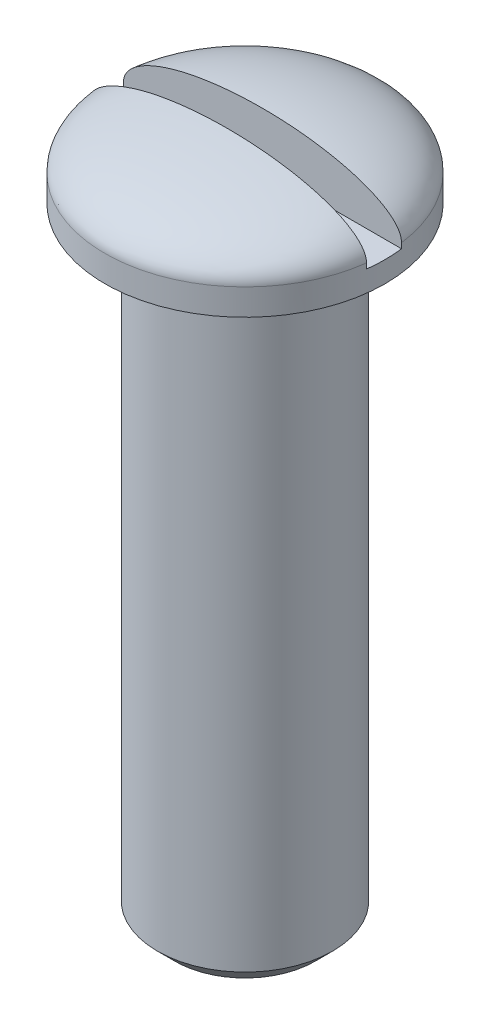
SolidWorks part; units mm, degrees
material "AISI 1045 Stal walcowana na zimno"
ref_plane "Płaszczyzna przednia" through (0, 0, 0) normal (0, 0, 1) x (1, 0, 0)
ref_plane "Płaszczyzna górna" through (0, 0, 0) normal (0, 1, 0) x (1, 0, 0)
ref_plane "Płaszczyzna prawa" through (0, 0, 0) normal (1, 0, 0) x (0, 0, -1)
sketch "Szkic1" plane through (0, 0, 0) normal (0, 0, 1) x (1, 0, 0)
  line L0 (0, 0) -> (0, 39.7) construction
  line L1 (0, 0) -> (5, 0)
  line L2 (5, 0) -> (5, 35.5)
  line L3 (5, 35.5) -> (8, 35.5)
  line L4 (8, 35.5) -> (8, 37)
  line L5 (0, 0) -> (0, 39.7)
  line L6 (5, 7) -> (0, 7) construction
  line L7 (8, 37) -> (8, 39.7) construction
  ellipse E0 centre (0, 37) end of major axis (8, 37) minor radius 2.7 (8, 37) -> (0, 39.7) ccw
  dimension "D1" = 35.5
  dimension "D2" = 10
  dimension "D3" = 16
  dimension "D4" = 1.5
  dimension "D5" = 2.7
  dimension "D6" = 28.5
revolve "Obrót1" add sketch "Szkic1" angle 360 about L0
cosmetic thread "Oznaczenie gwintu1" parameters "D1"=9, "D2"=8.344
chamfer "Sfazowanie1" distance 1 angle 45 1 edges at (5, 0, 0)
thread "Gwint2" pitch 1.5 start angle 0, offset 0, length 6, pitch 1.5, diameter 10
ref_plane "Płaszczyzna3" through (5, 1, 0) normal (0, 0, 1) x (1, 0, 0)
sketch "Profil gwintu3" plane through (5, 1, 0) normal (0, 0, 1) x (1, 0, 0)
  line L0 (0, 0) -> (0, 1.5) construction
  line L1 (0, 0) -> (0.8119, 0.4687)
  line L2 (0.8119, 0.4687) -> (0.8119, 0.6562)
  line L3 (0.8119, 0.6562) -> (0, 1.125)
  line L4 (0.8119, 0.5625) -> (0, 0.5625) construction
  line L11 (0, 0) -> (0, 1.125)
  point P2 (0, 0)
  dimension "Pitch" = 1.5
  dimension "Profile_Angle" = 60
  dimension "Profile_Land" = 0.1875
  dimension "Profile_Height" = 0.8119
ref_plane "Płaszczyzna4" through (0, 39.7, 0) normal (0, 1, 0) x (1, 0, 0)
sketch "Szkic14" plane through (0, 39.7, 0) normal (0, 1, 0) x (1, 0, 0)
  line L0 (5, 0) -> (8, 0) construction
  line L1 (-8, -1) -> (8, -1)
  line L2 (-8, -1) -> (-8, 1)
  line L3 (-8, 1) -> (8, 1)
  line L4 (8, -1) -> (8, 1)
  line L5 (-8, -1) -> (8, 1) construction
  line L6 (-8, 1) -> (8, -1) construction
  line L7 (0, 0) -> (8, 0) construction
  point P0 (0, 0)
  point P10 (8, 0)
  dimension "D1" = 2
extrude "Wytnij-wyciągnięcie1" cut sketch "Szkic14" against normal blind 3
